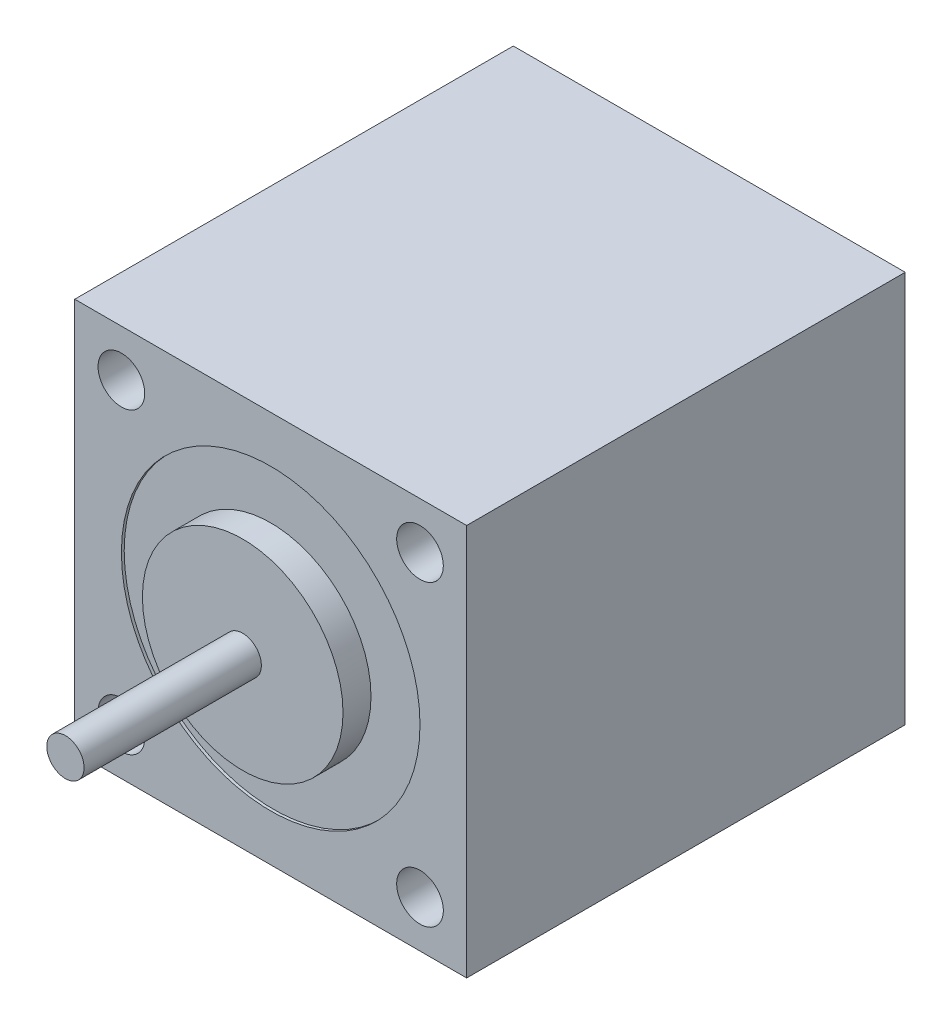
SolidWorks part; units mm, degrees
ref_plane "Front Plane" through (0, 0, 0) normal (0, 0, 1) x (1, 0, 0)
ref_plane "Top Plane" through (0, 0, 0) normal (0, 1, 0) x (1, 0, 0)
ref_plane "Right Plane" through (0, 0, 0) normal (1, 0, 0) x (0, 0, -1)
sketch "Sketch1" plane through (0, 0, 0) normal (0, 0, 1) x (1, 0, 0)
  line L1 (-21, -21) -> (21, -21)
  line L2 (-21, -21) -> (-21, 21)
  line L3 (-21, 21) -> (21, 21)
  line L4 (21, -21) -> (21, 21)
  line L5 (-21, -21) -> (21, 21) construction
  line L6 (-21, 21) -> (21, -21) construction
  point P0 (0, 0)
  dimension "D1" = 42
  dimension "D2" = 42
extrude "Boss-Extrude1" add sketch "Sketch1" along normal blind 47
sketch "Sketch2" plane through (0, 0, 47) normal (0, 0, 1) x (1, 0, 0)
  line L6 (0, -23.1) -> (0, 23.1) construction
  line L7 (23.1, 0) -> (-23.1, 0) construction
  circle A0 centre (16, 16) radius 2.5
  circle A1 centre (-16, 16) radius 2.5
  circle A2 centre (16, -16) radius 2.5
  circle A3 centre (-16, -16) radius 2.5
extrude "Cut-Extrude1" cut sketch "Sketch2" against normal blind 47
sketch "Sketch12" plane through (0, 0, 47) normal (0, 0, 1) x (1, 0, 0)
  circle A0 centre (0, 0) radius 16
sketch "Sketch13" plane through (0, 0, 47) normal (0, 0, 1) x (1, 0, 0)
  circle A0 centre (0, 0) radius 10.75
extrude "Boss-Extrude5" add sketch "Sketch13" along normal blind 3
extrude "Cut-Extrude2" cut sketch "Sketch12" against normal blind 0.3
sketch "Sketch14" plane through (0, 0, 50) normal (0, 0, 1) x (1, 0, 0)
  circle A0 centre (0, 0) radius 2
extrude "Boss-Extrude6" add sketch "Sketch14" along normal blind 19
